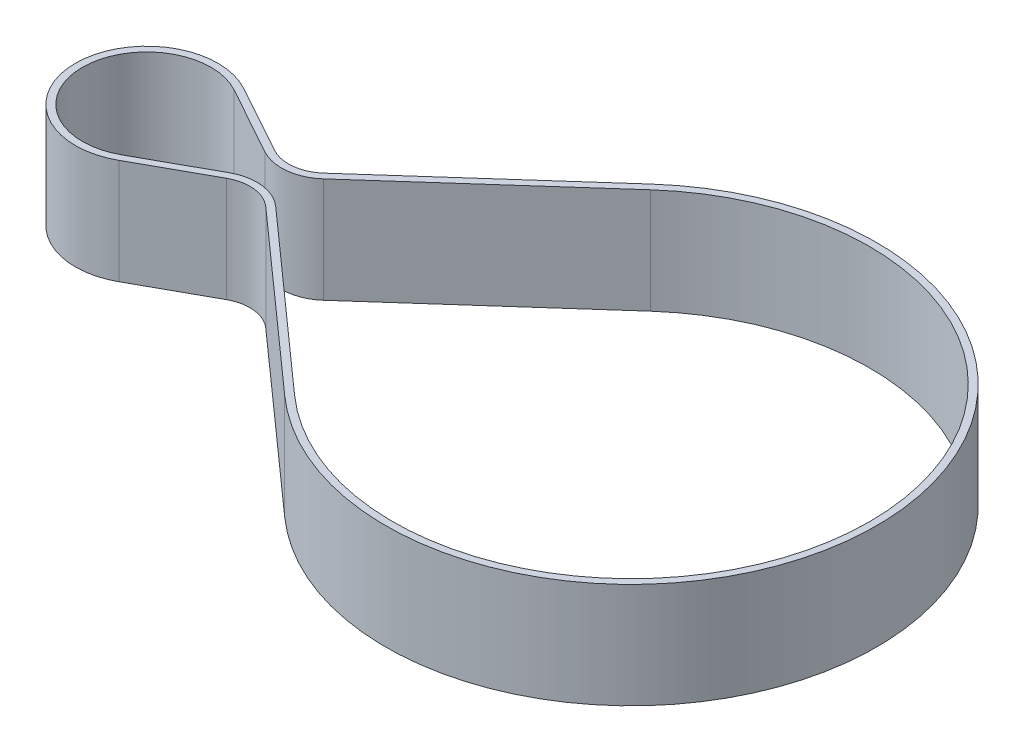
SolidWorks part; units mm, degrees
ref_plane "Front Plane" through (0, 0, 0) normal (0, 0, 1) x (1, 0, 0)
ref_plane "Top Plane" through (0, 0, 0) normal (0, 1, 0) x (1, 0, 0)
ref_plane "Right Plane" through (0, 0, 0) normal (1, 0, 0) x (0, 0, -1)
sketch "Sketch1" plane through (0, 0, 0) normal (0, 1, 0) x (1, 0, 0)
  line L0 (-46.0535, 11.0463) -> (-36.1619, 5.5807)
  line L1 (-45.5699, 11.9215) -> (-35.6783, 6.456)
  line L2 (-46.0535, -5.0062) -> (-36.1619, 0.4593)
  line L3 (-45.5699, -5.8815) -> (-35.6783, -0.416)
  line L4 (-29.3603, 7.1629) -> (-4.667, 29.1563)
  line L5 (-29.3603, -1.1228) -> (-4.667, -23.1163)
  line L6 (-28.6952, 6.4161) -> (-4.0019, 28.4096)
  line L7 (-28.6952, -0.3761) -> (-4.0019, -22.3695)
  circle A0 centre (-50.4884, 3.02) radius 9.17
  circle A1 centre (-50.4884, 3.02) radius 10.17
  circle A2 centre (18.6116, 3.02) radius 34
  circle A3 centre (18.6116, 3.02) radius 35
  circle A4 centre (-33.0184, -5.23) radius 5.5
  circle A5 centre (-33.0184, -5.23) radius 6.5
  circle A6 centre (-33.0184, 11.27) radius 5.5
  circle A7 centre (-33.0184, 11.27) radius 6.5
extrude "Boss-Extrude1" add sketch "Sketch1" along normal blind 15 contours A3 L6 A2 L7 | A5 L5 A3 L7 | A7 L6 A3 L4 | L5 A5 L3 A4 | A7 L4 A6 L1 | A7 L1 A1 L0 | A5 L2 A1 L3 | A1 L2 A0 L0
